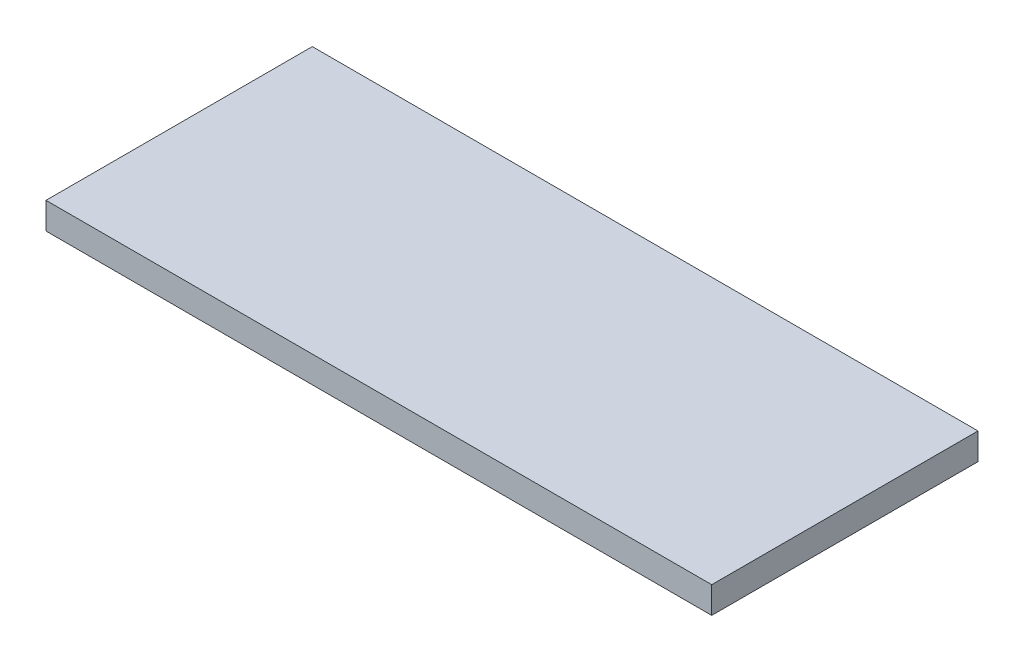
SolidWorks part; units mm, degrees
ref_plane "Front Plane" through (0, 0, 0) normal (0, 0, 1) x (1, 0, 0)
ref_plane "Top Plane" through (0, 0, 0) normal (0, 1, 0) x (1, 0, 0)
ref_plane "Right Plane" through (0, 0, 0) normal (1, 0, 0) x (0, 0, -1)
sketch "Sketch1" plane through (0, 0, 0) normal (0, 1, 0) x (1, 0, 0)
  line L1 (-25, -10) -> (25, -10)
  line L2 (-25, -10) -> (-25, 10)
  line L3 (-25, 10) -> (25, 10)
  line L4 (25, -10) -> (25, 10)
  line L5 (-25, -10) -> (25, 10) construction
  line L6 (-25, 10) -> (25, -10) construction
  point P0 (0, 0)
  dimension "D1" = 20
  dimension "D2" = 50
extrude "Boss-Extrude1" add sketch "Sketch1" along normal blind 2
